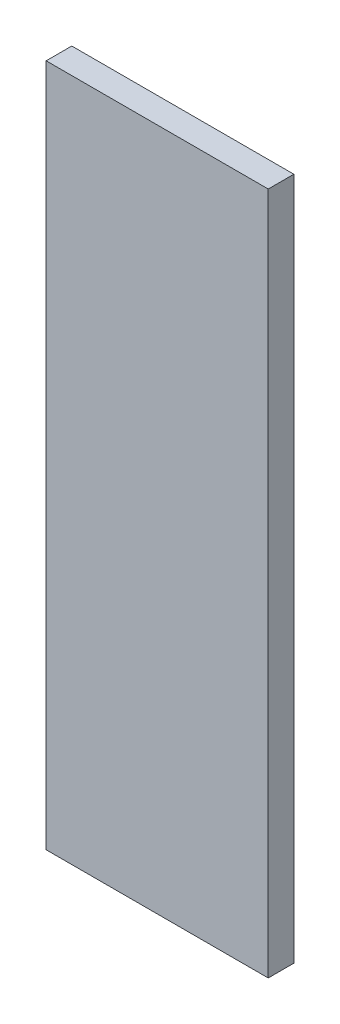
SolidWorks part; units mm, degrees
ref_plane "Front Plane" through (0, 0, 0) normal (0, 0, 1) x (1, 0, 0)
ref_plane "Top Plane" through (0, 0, 0) normal (0, 1, 0) x (1, 0, 0)
ref_plane "Right Plane" through (0, 0, 0) normal (1, 0, 0) x (0, 0, -1)
sketch "Sketch1" plane through (0, 0, 0) normal (0, 0, 1) x (1, 0, 0)
  line L1 (-49.2574, 89.9404) -> (115.8426, 89.9404)
  line L2 (-49.2574, 89.9404) -> (-49.2574, -418.0596)
  line L3 (-49.2574, -418.0596) -> (115.8426, -418.0596)
  line L4 (115.8426, 89.9404) -> (115.8426, -418.0596)
  line L5 (-49.2574, 89.9404) -> (115.8426, -418.0596) construction
  line L6 (-49.2574, -418.0596) -> (115.8426, 89.9404) construction
  point P0 (33.2926, -164.0596)
extrude "Boss-Extrude1" add sketch "Sketch1" along normal blind 19.05 contours L2 L1 L4 L3
